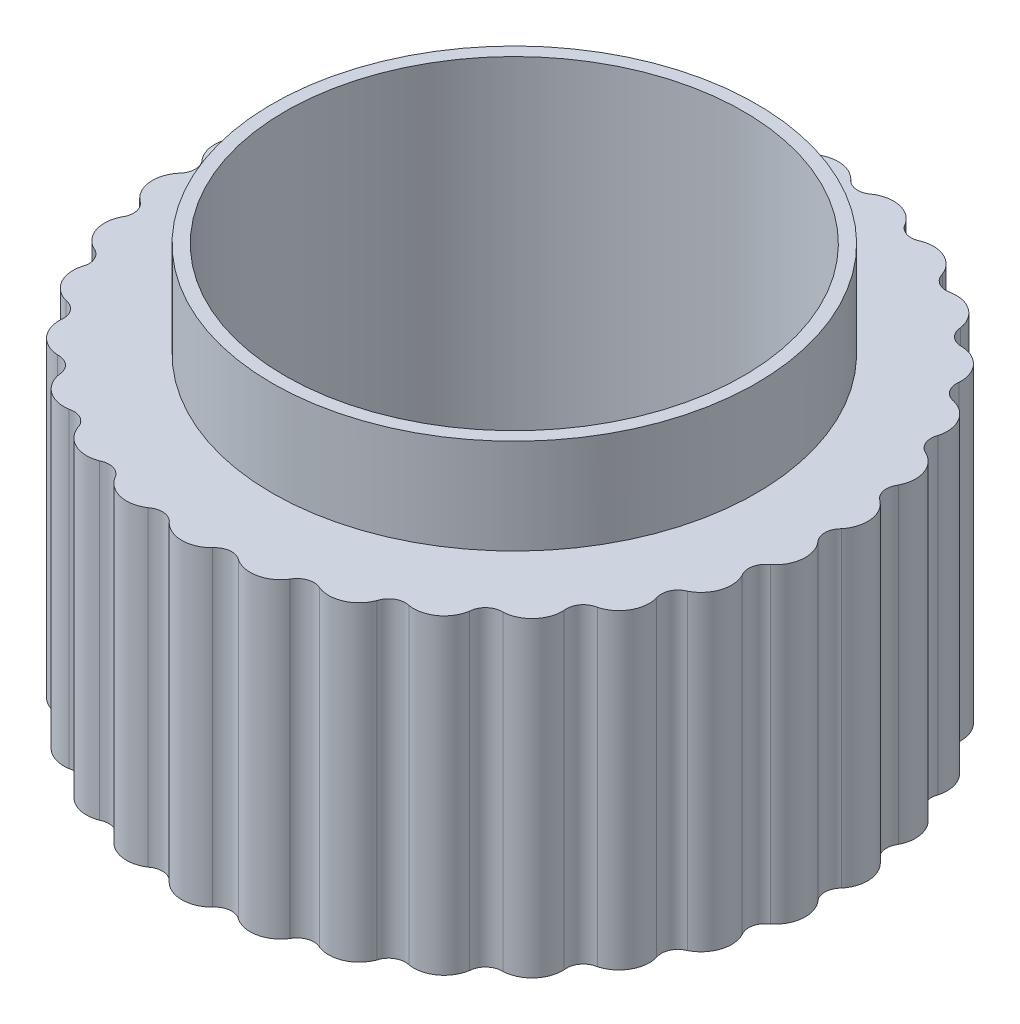
SolidWorks part; units mm, degrees
ref_plane "Front Plane" through (0, 0, 0) normal (0, 0, 1) x (1, 0, 0)
ref_plane "Top Plane" through (0, 0, 0) normal (0, 1, 0) x (1, 0, 0)
ref_plane "Right Plane" through (0, 0, 0) normal (1, 0, 0) x (0, 0, -1)
sketch "Sketch1" plane through (0, 0, 0) normal (0, 0, 1) x (1, 0, 0)
  line L0 (127, 271.5) -> (635, 271.5) construction
  line L1 (434.0182, 194.9999) -> (444.0182, 194.9999)
  line L2 (509.9999, 194.9999) -> (501.0003, 301.998)
  line L3 (452.9992, 301.9988) -> (442.9992, 301.9988)
  line L4 (442.9992, 301.9988) -> (434.0182, 205.8959)
  line L5 (452.9992, 301.9988) -> (445.8146, 204.9999)
  line L6 (419.2726, 0) -> (419.2726, 194.9999)
  line L7 (442.9992, 301.9988) -> (452.9992, 301.9986) construction
  line L8 (501.0003, 301.998) -> (471.9998, 301.9984) construction
  line L9 (471.9998, 301.9984) -> (471.9998, 194.9999) construction
  line L10 (434.0182, 194.9999) -> (434.0182, 205.8959)
  line L11 (444.0182, 204.9999) -> (445.8146, 204.9999) construction
  line L12 (444.0182, 194.9999) -> (444.0182, 204.9999)
  line L13 (445.8146, 204.9999) -> (444.0182, 204.9999)
  line L14 (471.9998, 301.9984) -> (501.0003, 301.998) construction
  dimension "D1" = 106.9988
ref_plane "Plane2" through (0, 195, 0) normal (0, 1, 0) x (1, 0, 0)
sketch "Sketch3" plane through (0, 195, 0) normal (0, 1, 0) x (1, 0, 0)
  line L0 (434.0182, 0) -> (444.0182, 0) construction
  circle A0 centre (471.5, 0) radius 38
sketch "Sketch4" plane through (0, 0, 0) normal (0, 0, 1) x (1, 0, 0)
ref_plane "Plane3" through (0, 302, 0) normal (0, 1, 0) x (1, 0, 0)
sketch "Sketch5" plane through (0, 0, 0) normal (0, 0, 1) x (1, 0, 0)
  line L0 (294.0971, 237.4575) -> (406.5132, 237.4575)
  line L1 (433.6657, 143.7869) -> (509.5647, 143.7869)
  point P0 (294.0971, 237.4575)
sketch "Sketch7" plane through (0, 195, 0) normal (0, 1, 0) x (1, 0, 0)
  line L0 (469, 0) -> (474, 0) construction
  line L1 (501.0003, 0) -> (471.9998, 0) construction
  line L2 (469, 12.9436) -> (469, -45.9693) construction
  line L3 (474, 9.3679) -> (474, -40.0099) construction
  circle A0 centre (471.5, 0) radius 38 construction
  circle A1 centre (471.5, 0) radius 37 construction
  arc A2 (469, -36.9154) -> (474, -36.9154) centre (471.5, -34.4154) ccw
  arc A3 (461.3795, -35.589) -> (466.2702, -36.6285) centre (464.3446, -33.6634) ccw
  arc A4 (454.2013, -32.7071) -> (458.769, -34.7408) centre (457.502, -31.4401) ccw
  arc A5 (447.7791, -28.3958) -> (451.8242, -31.3347) centre (451.2711, -27.8427) ccw
  arc A6 (442.3937, -22.8434) -> (445.7393, -26.5591) centre (445.9243, -23.0284) ccw
  arc A7 (438.2803, -16.2927) -> (440.7803, -20.6228) centre (441.6954, -17.2077) ccw
  arc A8 (435.6188, -9.0299) -> (437.1639, -13.7851) centre (438.769, -10.635) ccw
  arc A9 (434.5255, -1.3724) -> (435.0481, -6.345) centre (437.2731, -3.5974) ccw
  arc A10 (435.0481, 6.345) -> (434.5255, 1.3724) centre (437.2731, 3.5974) ccw
  arc A11 (437.1639, 13.7851) -> (435.6188, 9.0299) centre (438.769, 10.635) ccw
  arc A12 (440.7803, 20.6228) -> (438.2803, 16.2927) centre (441.6954, 17.2077) ccw
  arc A13 (445.7393, 26.5591) -> (442.3937, 22.8434) centre (445.9243, 23.0284) ccw
  arc A14 (451.8242, 31.3347) -> (447.7791, 28.3958) centre (451.2711, 27.8427) ccw
  arc A15 (458.769, 34.7408) -> (454.2013, 32.7071) centre (457.502, 31.4401) ccw
  arc A16 (466.2702, 36.6285) -> (461.3795, 35.589) centre (464.3446, 33.6634) ccw
  arc A17 (474, 36.9154) -> (469, 36.9154) centre (471.5, 34.4154) ccw
  arc A18 (481.6205, 35.589) -> (476.7298, 36.6285) centre (478.6554, 33.6634) ccw
  arc A19 (488.7987, 32.7071) -> (484.231, 34.7408) centre (485.498, 31.4401) ccw
  arc A20 (495.2209, 28.3958) -> (491.1758, 31.3347) centre (491.7289, 27.8427) ccw
  arc A21 (500.6064, 22.8434) -> (497.2607, 26.5591) centre (497.0757, 23.0284) ccw
  arc A22 (504.7197, 16.2927) -> (502.2197, 20.6228) centre (501.3047, 17.2077) ccw
  arc A23 (507.3812, 9.0299) -> (505.8361, 13.7851) centre (504.231, 10.635) ccw
  arc A24 (508.4745, 1.3724) -> (507.9519, 6.345) centre (505.7269, 3.5974) ccw
  arc A25 (507.9519, -6.345) -> (508.4745, -1.3724) centre (505.7269, -3.5974) ccw
  arc A26 (505.8361, -13.7851) -> (507.3812, -9.0299) centre (504.231, -10.635) ccw
  arc A27 (502.2197, -20.6228) -> (504.7197, -16.2927) centre (501.3047, -17.2077) ccw
  arc A28 (497.2607, -26.5591) -> (500.6064, -22.8434) centre (497.0757, -23.0284) ccw
  arc A29 (491.1758, -31.3347) -> (495.2209, -28.3958) centre (491.7289, -27.8427) ccw
  arc A30 (484.231, -34.7408) -> (488.7987, -32.7071) centre (485.498, -31.4401) ccw
  arc A31 (476.7298, -36.6285) -> (481.6205, -35.589) centre (478.6554, -33.6634) ccw
  arc A32 (434.5255, 1.3724) -> (434.5255, -1.3724) centre (433.1531, 0) cw
  arc A33 (435.6188, 9.0299) -> (435.0481, 6.345) centre (433.991, 7.9728) cw
  arc A34 (438.2803, 16.2927) -> (437.1639, 13.7851) centre (436.4683, 15.5971) cw
  arc A35 (442.3937, 22.8434) -> (440.7803, 20.6228) centre (440.4767, 22.5398) cw
  arc A36 (447.7791, 28.3958) -> (445.7393, 26.5591) centre (445.8409, 28.4973) cw
  arc A37 (454.2013, 32.7071) -> (451.8242, 31.3347) centre (452.3265, 33.2094) cw
  arc A38 (461.3795, 35.589) -> (458.769, 34.7408) centre (459.6501, 36.4701) cw
  arc A39 (469, 36.9154) -> (466.2702, 36.6285) centre (467.4917, 38.1369) cw
  arc A40 (476.7298, 36.6285) -> (474, 36.9154) centre (475.5084, 38.1369) cw
  arc A41 (484.231, 34.7408) -> (481.6205, 35.589) centre (483.3499, 36.4701) cw
  arc A42 (491.1758, 31.3347) -> (488.7987, 32.7071) centre (490.6735, 33.2094) cw
  arc A43 (497.2607, 26.5591) -> (495.2209, 28.3958) centre (497.1591, 28.4973) cw
  arc A44 (502.2197, 20.6228) -> (500.6064, 22.8434) centre (502.5233, 22.5398) cw
  arc A45 (505.8361, 13.7851) -> (504.7197, 16.2927) centre (506.5317, 15.5971) cw
  arc A46 (507.9519, 6.345) -> (507.3812, 9.0299) centre (509.009, 7.9728) cw
  arc A47 (508.4745, -1.3724) -> (508.4745, 1.3724) centre (509.847, 0) cw
  arc A48 (507.3812, -9.0299) -> (507.9519, -6.345) centre (509.009, -7.9728) cw
  arc A49 (504.7197, -16.2927) -> (505.8361, -13.7851) centre (506.5317, -15.5971) cw
  arc A50 (500.6064, -22.8434) -> (502.2197, -20.6228) centre (502.5233, -22.5398) cw
  arc A51 (495.2209, -28.3958) -> (497.2607, -26.5591) centre (497.1591, -28.4973) cw
  arc A52 (488.7987, -32.7071) -> (491.1758, -31.3347) centre (490.6735, -33.2094) cw
  arc A53 (481.6205, -35.589) -> (484.231, -34.7408) centre (483.3499, -36.4701) cw
  arc A54 (474, -36.9154) -> (476.7298, -36.6285) centre (475.5084, -38.1369) cw
  arc A55 (466.2702, -36.6285) -> (469, -36.9154) centre (467.4917, -38.1369) cw
  arc A56 (458.769, -34.7408) -> (461.3795, -35.589) centre (459.6501, -36.4701) cw
  arc A57 (451.8242, -31.3347) -> (454.2013, -32.7071) centre (452.3265, -33.2094) cw
  arc A58 (445.7393, -26.5591) -> (447.7791, -28.3958) centre (445.8409, -28.4973) cw
  arc A59 (440.7803, -20.6228) -> (442.3937, -22.8434) centre (440.4767, -22.5398) cw
  arc A60 (437.1639, -13.7851) -> (438.2803, -16.2927) centre (436.4683, -15.5971) cw
  arc A61 (435.0481, -6.345) -> (435.6188, -9.0299) centre (433.991, -7.9728) cw
  circle A62 centre (471.5, 0) radius 27.4931
  point P9 (471.5, 0)
  point P106 (471.5, 0)
  point P194 (471.5, 0)
  dimension "D1" = 30
  dimension "D2" = 30
extrude "Boss-Extrude2" add sketch "Sketch7" against normal blind 36
sketch "Sketch8" plane through (0, 195, 0) normal (0, 1, 0) x (1, 0, 0)
  circle A0 centre (471.9998, 0) radius 27.9928
  circle A1 centre (471.9998, 0) radius 26.5024
extrude "Boss-Extrude3" add sketch "Sketch8" along normal blind 11 and the other way blind 36
